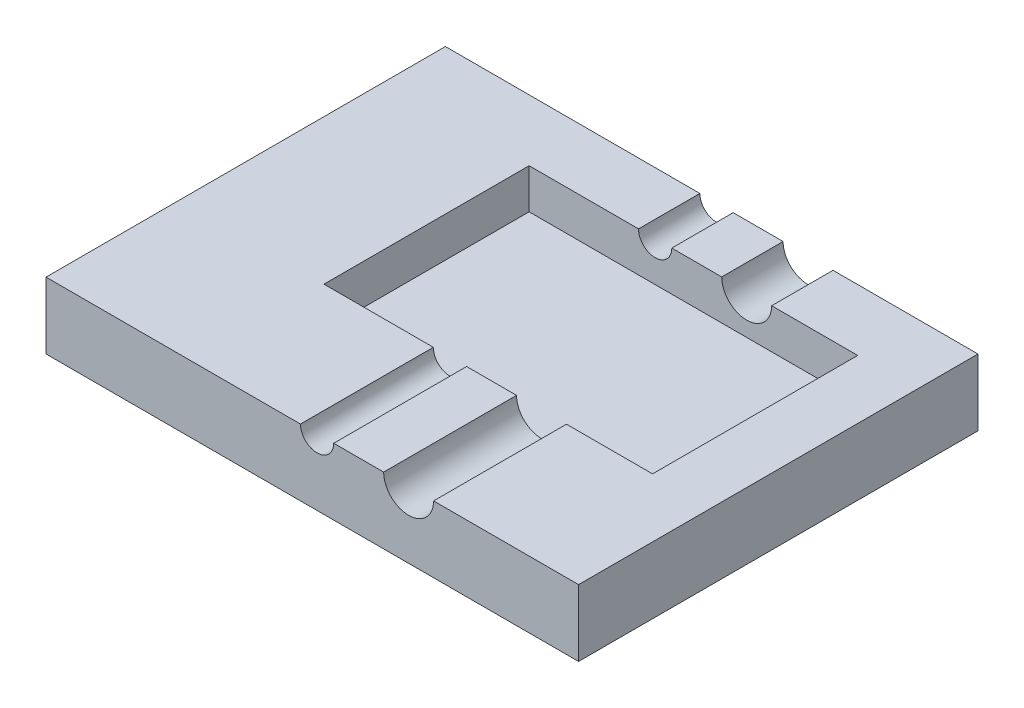
SolidWorks part; units mm, degrees
ref_plane "Front Plane" through (0, 0, 0) normal (0, 0, 1) x (1, 0, 0)
ref_plane "Top Plane" through (0, 0, 0) normal (0, 1, 0) x (1, 0, 0)
ref_plane "Right Plane" through (0, 0, 0) normal (1, 0, 0) x (0, 0, -1)
sketch "Sketch1" plane through (0, 0, 0) normal (0, 1, 0) x (1, 0, 0)
  line L1 (-50.8, -8.038) -> (50.8, -8.038)
  line L2 (-50.8, -8.038) -> (-50.8, 68.162)
  line L3 (-50.8, 68.162) -> (50.8, 68.162)
  line L4 (50.8, -8.038) -> (50.8, 68.162)
  line L5 (-50.8, -8.038) -> (50.8, 68.162) construction
  line L6 (-50.8, 68.162) -> (50.8, -8.038) construction
  point P0 (0, 30.062)
  dimension "D1" = 101.6
  dimension "D2" = 76.2
extrude "Boss-Extrude1" add sketch "Sketch1" along normal blind 12.7
sketch "Sketch4" plane through (0, 12.7, 0) normal (0, 1, 0) x (1, 0, 0)
  line L1 (-23.125, 17.3143) -> (39.5601, 17.3143)
  line L2 (-23.125, 17.3143) -> (-23.125, 56.453)
  line L3 (-23.125, 56.453) -> (39.5601, 56.453)
  line L4 (39.5601, 17.3143) -> (39.5601, 56.453)
  line L5 (-23.125, 17.3143) -> (39.5601, 56.453) construction
  line L6 (-23.125, 56.453) -> (39.5601, 17.3143) construction
  point P0 (8.2175, 36.8836)
extrude "Cut-Extrude2" cut sketch "Sketch4" against normal blind 7.62 contours L1 L4 L3 L2
sketch "Sketch5" plane through (0, 0, 8.038) normal (0, 0, 1) x (1, 0, 0)
  line L0 (-50.8, 12.7) -> (50.8, 12.7) construction
  circle A0 centre (0.9171, 12.7) radius 3.175
  circle A1 centre (18.3796, 12.7) radius 4.7625
  dimension "D1" = 6.35
  dimension "D2" = 9.525
  dimension "D3" = 17.4625
extrude "Cut-Extrude3" cut sketch "Sketch5" against normal through all
